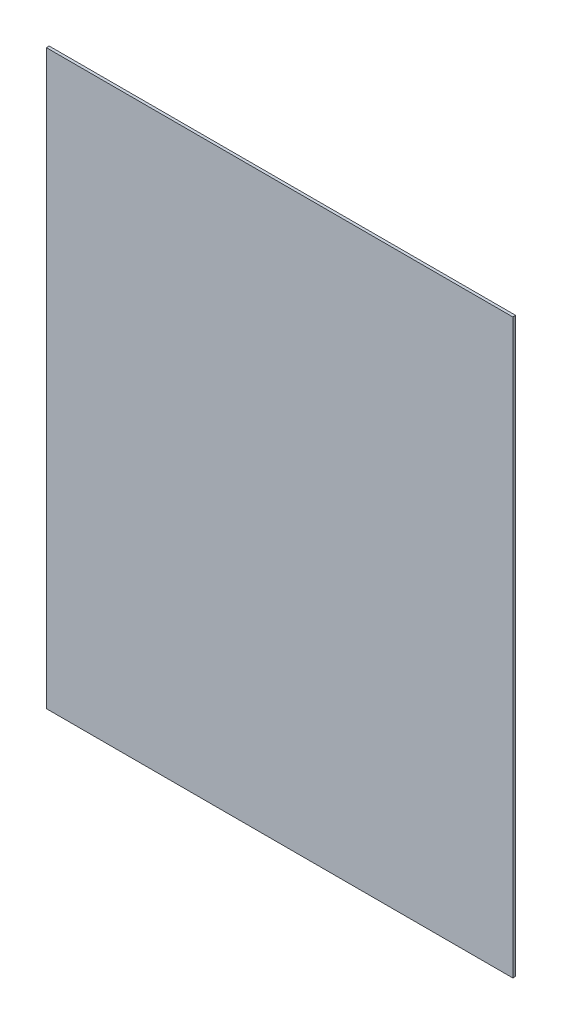
SolidWorks part; units mm, degrees
ref_plane "Front Plane" through (0, 0, 0) normal (0, 0, 1) x (1, 0, 0)
ref_plane "Top Plane" through (0, 0, 0) normal (0, 1, 0) x (1, 0, 0)
ref_plane "Right Plane" through (0, 0, 0) normal (1, 0, 0) x (0, 0, -1)
sketch "Sketch1" plane through (0, 0, 0) normal (0, 0, 1) x (1, 0, 0)
  line L0 (-0.825, 1.025) -> (0.825, 1.025)
  line L1 (0.825, 1.025) -> (0.825, -1)
  line L2 (0.825, -1) -> (-0.825, -1)
  line L3 (-0.825, -1) -> (-0.825, 1.025)
extrude "Component_Outline" add sketch "Sketch1" along normal blind 0.01 separate body
sketch3d "3DSketch1"
  line L0 (0, 0, 0) -> (1, 0, 0)
  line L1 (0, 0, 0) -> (0, 1, 0)
  line L2 (0, 0, 0) -> (0, 0, 1)
  point P0 (0, 0, 0)
